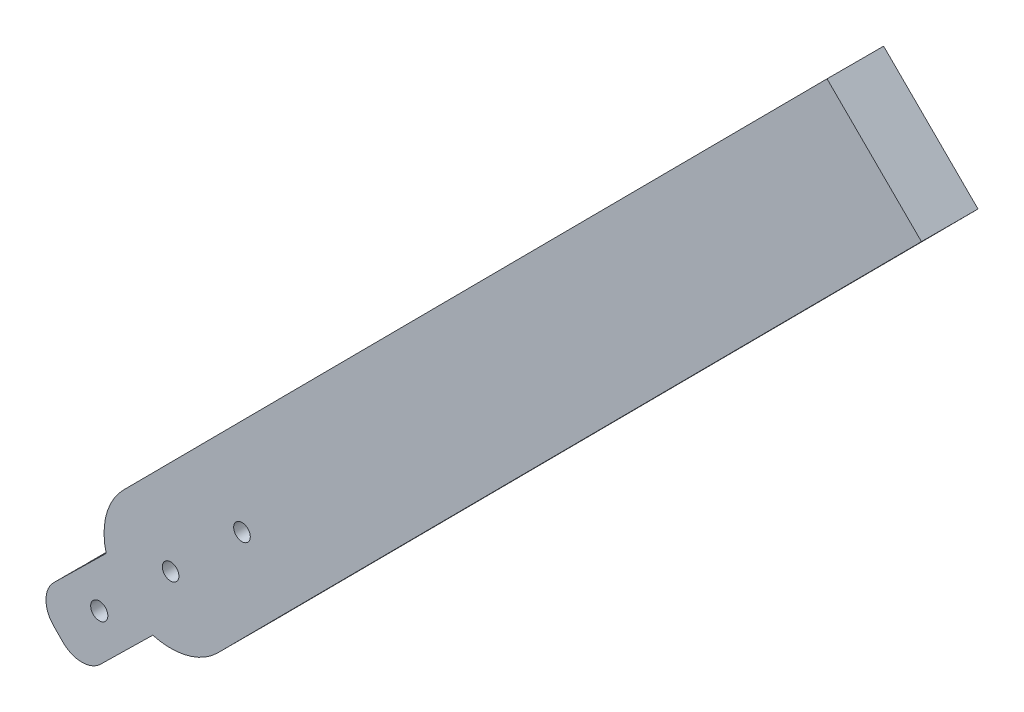
SolidWorks part; units mm, degrees
ref_plane "前视基准面" through (0, 0, 0) normal (0, 0, 1) x (1, 0, 0)
ref_plane "上视基准面" through (0, 0, 0) normal (0, 1, 0) x (1, 0, 0)
ref_plane "右视基准面" through (0, 0, 0) normal (1, 0, 0) x (0, 0, -1)
sketch "草图1" plane through (0, 0, 0) normal (0, 0, 1) x (1, 0, 0)
  line L0 (-14.1852, 14.0989) -> (14.1852, -14.0989)
  line L1 (-14.1852, 14.0989) -> (197.2984, 226.8774)
  line L2 (14.1852, -14.0989) -> (225.6689, 198.6795)
  line L3 (197.2984, 226.8774) -> (225.6689, 198.6795)
  line L4 (-19.366, -4.9957) -> (-5.3566, -19.2693)
  line L5 (-19.366, -4.9957) -> (-35.067, -20.4061)
  line L6 (-5.3566, -19.2693) -> (-21.0576, -34.6797)
  line L7 (-35.1727, -31.7193) -> (-32.3708, -34.574)
  arc A0 (-14.1852, 14.0989) -> (14.1852, -14.0989) centre (0, 0) ccw
  arc A1 (-35.067, -20.4061) -> (-35.1727, -31.7193) centre (-29.4632, -26.1155) ccw
  arc A2 (-21.0576, -34.6797) -> (-32.3708, -34.574) centre (-26.6613, -28.9703) cw
  point P12 (-40.7764, -26.0099)
  point P15 (-26.767, -40.2835)
  dimension "D1" = 20
  dimension "D7" = 8
  dimension "D8" = 8
  dimension "D2" = 300
  dimension "D3" = 40
  dimension "D4" = 28.3705
  dimension "D5" = 20
  dimension "D6" = 30
extrude "凸台-拉伸1" add sketch "草图1" along normal blind 17 contours L0 A0 | L3 L1 L0 L2 | L4 L5 A1 L7 A2 L6
sketch "草图2" plane through (0, 0, 17) normal (0, 0, 1) x (1, 0, 0)
  line L6 (14.1852, -14.0989) -> (225.6689, 198.6795)
  line L7 (225.6689, 198.6795) -> (197.2984, 226.8774)
  line L8 (197.2984, 226.8774) -> (-14.1852, 14.0989)
  line L9 (-19.366, -4.9957) -> (-35.067, -20.4061)
  line L10 (-35.1727, -31.7193) -> (-32.3708, -34.574)
  line L11 (-21.0576, -34.6797) -> (-5.3566, -19.2693)
  line L12 (14.1852, -14.0989) -> (225.6689, 198.6795)
  line L13 (225.6689, 198.6795) -> (197.2984, 226.8774)
  line L14 (197.2984, 226.8774) -> (-14.1852, 14.0989)
  line L15 (-19.366, -4.9957) -> (-35.067, -20.4061)
  line L16 (-35.1727, -31.7193) -> (-32.3708, -34.574)
  line L17 (-21.0576, -34.6797) -> (-5.3566, -19.2693)
  circle A0 centre (0, 0) radius 2.5
  arc A4 (-5.3566, -19.2693) -> (14.1852, -14.0989) centre (0, 0) ccw
  arc A5 (-14.1852, 14.0989) -> (-19.366, -4.9957) centre (0, 0) ccw
  arc A6 (-35.067, -20.4061) -> (-35.1727, -31.7193) centre (-29.4632, -26.1155) ccw
  arc A7 (-32.3708, -34.574) -> (-21.0576, -34.6797) centre (-26.6613, -28.9703) ccw
  arc A8 (-5.3566, -19.2693) -> (14.1852, -14.0989) centre (0, 0) ccw
  arc A9 (-14.1852, 14.0989) -> (-19.366, -4.9957) centre (0, 0) ccw
  arc A10 (-35.067, -20.4061) -> (-35.1727, -31.7193) centre (-29.4632, -26.1155) ccw
  arc A11 (-32.3708, -34.574) -> (-21.0576, -34.6797) centre (-26.6613, -28.9703) ccw
  dimension "D2" = 5
  dimension "D1" = 0
extrude "切除-拉伸1" cut sketch "草图2" against normal through all contours A0
sketch "草图3" plane through (0, 0, 17) normal (0, 0, 1) x (1, 0, 0)
  line L2 (0, 0) -> (-21.4463, -20.9775) construction
  circle A0 centre (-21.4463, -20.9775) radius 2.5835
  dimension "D1" = 30
extrude "切除-拉伸2" cut sketch "草图3" against normal through all
sketch "草图4" plane through (-33.7717, -33.1467, 0) normal (-0.7137, -0.7005, 0) x (0, 0, 1)
  line L1 (8.5, 2.9426) -> (8.5, -3.6506) construction
  line L2 (6.9, 27.5265) -> (10.1, 27.5265)
  line L3 (6.9, 27.5265) -> (6.9, -27.5265)
  line L4 (0, 2) -> (0, -2)
  line L5 (0, -2) -> (17, -2)
  line L6 (17, -2) -> (17, 2)
  line L7 (17, 2) -> (0, 2)
  line L8 (0, 2) -> (0, -2)
  line L9 (0, -2) -> (17, -2)
  line L10 (17, -2) -> (17, 2)
  line L11 (17, 2) -> (0, 2)
  line L12 (6.9, -27.5265) -> (10.1, -27.5265)
  line L13 (10.1, 27.5265) -> (10.1, -27.5265)
  line L14 (6.9, 27.5265) -> (10.1, -27.5265) construction
  line L15 (6.9, -27.5265) -> (10.1, 27.5265) construction
  point P2 (8.5, 0)
  line M8 (0, -2) -> (17, -2)
  dimension "D2" = 3.2
  dimension "D1" = 0
extrude "切除-拉伸3" cut sketch "草图4" against normal blind 40 contours L13 L3 L12 M8 | L13 L2 L3 L11 | L13 L11 L3 M8
sketch "草图5" plane through (0, 0, 17) normal (0, 0, 1) x (1, 0, 0)
  line L0 (0, 0) -> (-21.4463, -20.9775) construction
  line L1 (0, 0) -> (21.4463, 20.9775) construction
  line L6 (14.1852, -14.0989) -> (225.6689, 198.6795)
  line L7 (225.6689, 198.6795) -> (197.2984, 226.8774)
  line L8 (197.2984, 226.8774) -> (-14.1852, 14.0989)
  line L9 (-19.366, -4.9957) -> (-35.067, -20.4061)
  line L10 (-35.1727, -31.7193) -> (-32.3708, -34.574)
  line L11 (-21.0576, -34.6797) -> (-5.3566, -19.2693)
  line L12 (14.1852, -14.0989) -> (225.6689, 198.6795)
  line L13 (225.6689, 198.6795) -> (197.2984, 226.8774)
  line L14 (197.2984, 226.8774) -> (-14.1852, 14.0989)
  line L15 (-19.366, -4.9957) -> (-35.067, -20.4061)
  line L16 (-35.1727, -31.7193) -> (-32.3708, -34.574)
  line L17 (-21.0576, -34.6797) -> (-5.3566, -19.2693)
  circle A0 centre (21.4463, 20.9775) radius 2.5
  arc A4 (-5.3566, -19.2693) -> (14.1852, -14.0989) centre (0, 0) ccw
  arc A5 (-14.1852, 14.0989) -> (-19.366, -4.9957) centre (0, 0) ccw
  arc A6 (-35.067, -20.4061) -> (-35.1727, -31.7193) centre (-29.4632, -26.1155) ccw
  arc A7 (-32.3708, -34.574) -> (-21.0576, -34.6797) centre (-26.6613, -28.9703) ccw
  arc A8 (-5.3566, -19.2693) -> (14.1852, -14.0989) centre (0, 0) ccw
  arc A9 (-14.1852, 14.0989) -> (-19.366, -4.9957) centre (0, 0) ccw
  arc A10 (-35.067, -20.4061) -> (-35.1727, -31.7193) centre (-29.4632, -26.1155) ccw
  arc A11 (-32.3708, -34.574) -> (-21.0576, -34.6797) centre (-26.6613, -28.9703) ccw
  dimension "D3" = 5
  dimension "D2" = 30
  dimension "D1" = 0
extrude "切除-拉伸4" cut sketch "草图5" against normal through all contours A0
sketch "草图6" plane through (0, 0, 17) normal (0, 0, 1) x (1, 0, 0)
  line L6 (14.1852, -14.0989) -> (225.6689, 198.6795)
  line L7 (225.6689, 198.6795) -> (197.2984, 226.8774)
  line L8 (197.2984, 226.8774) -> (-14.1852, 14.0989)
  line L9 (-19.366, -4.9957) -> (-35.067, -20.4061)
  line L10 (-35.1727, -31.7193) -> (-32.3708, -34.574)
  line L11 (-21.0576, -34.6797) -> (-5.3566, -19.2693)
  line L12 (14.1852, -14.0989) -> (225.6689, 198.6795)
  line L13 (225.6689, 198.6795) -> (197.2984, 226.8774)
  line L14 (197.2984, 226.8774) -> (-14.1852, 14.0989)
  line L15 (-19.366, -4.9957) -> (-35.067, -20.4061)
  line L16 (-35.1727, -31.7193) -> (-32.3708, -34.574)
  line L17 (-21.0576, -34.6797) -> (-5.3566, -19.2693)
  circle A0 centre (0, 0) radius 20
  arc A4 (-5.3566, -19.2693) -> (14.1852, -14.0989) centre (0, 0) ccw
  arc A5 (-14.1852, 14.0989) -> (-19.366, -4.9957) centre (0, 0) ccw
  arc A6 (-35.067, -20.4061) -> (-35.1727, -31.7193) centre (-29.4632, -26.1155) ccw
  arc A7 (-32.3708, -34.574) -> (-21.0576, -34.6797) centre (-26.6613, -28.9703) ccw
  arc A8 (-5.3566, -19.2693) -> (14.1852, -14.0989) centre (0, 0) ccw
  arc A9 (-14.1852, 14.0989) -> (-19.366, -4.9957) centre (0, 0) ccw
  arc A10 (-35.067, -20.4061) -> (-35.1727, -31.7193) centre (-29.4632, -26.1155) ccw
  arc A11 (-32.3708, -34.574) -> (-21.0576, -34.6797) centre (-26.6613, -28.9703) ccw
  dimension "D1" = 0
sketch "草图7" plane through (-14.1852, 14.0989, 0) normal (-0.7093, 0.7049, 0) x (0, 0, 1)
  line L0 (6.9, -7.0893) -> (10.1, -7.0893) construction
  line L1 (6.9, -7.0893) -> (6.9, 129.0303) construction
  line L2 (10.1, -7.0893) -> (10.1, 129.0303) construction
  line L3 (6.9, 129.0303) -> (10.1, 129.0303) construction
  line L4 (17, 0) -> (0, 0) construction
  line L5 (6.9, 7.0893) -> (10.1, 7.0893) construction
  line L6 (6.9, 7.0893) -> (10.1, 7.0893)
  line L7 (6.9, 7.0893) -> (6.9, 52.0893)
  line L8 (10.1, 7.0893) -> (10.1, 52.0893)
  line L9 (6.9, 52.0893) -> (10.1, 52.0893)
  dimension "D1" = 45
extrude "切除-拉伸5" cut sketch "草图7" against normal through all
fillet "圆角1" radius 5 4 edges at (19.1828, -9.0707, 8.5) (-9.1877, 19.1271, 8.5) (22.5349, 51.0439, 8.5) (50.9054, 22.846, 8.5)
